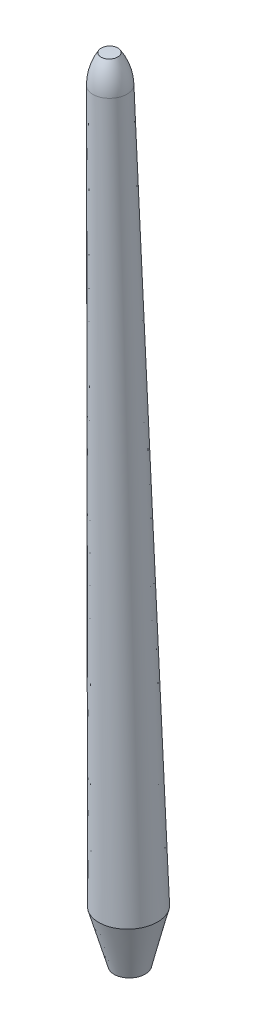
SolidWorks part; units mm, degrees
ref_plane "Alzado" through (0, 0, 0) normal (0, 0, 1) x (1, 0, 0)
ref_plane "Planta" through (0, 0, 0) normal (0, 1, 0) x (1, 0, 0)
ref_plane "Vista lateral" through (0, 0, 0) normal (1, 0, 0) x (0, 0, -1)
sketch "Croquis1" plane through (0, 0, 0) normal (0, 0, 1) x (1, 0, 0)
  line L0 (0, 0) -> (190.5, 0)
  line L1 (190.5, 0) -> (342.9736, 635)
  line L2 (0, 0) -> (-252.4067, 9652)
  line L4 (-252.4067, 9652) -> (-150.8067, 9652)
  line L5 (342.9736, 635) -> (-35.5514, 9311.6552)
  arc A1 (-35.5514, 9311.6552) -> (-150.8067, 9652) centre (-678.5233, 9283.6051) ccw
  dimension "D1" = 190.5
  dimension "D2" = 635
  dimension "D3" = 15
  dimension "D4" = 9652
  dimension "D5" = 1
revolve "Revolución2" add sketch "Croquis1" angle 360 about L2
sketch "Croquis2" plane through (0, 0, 0) normal (0, 0, 1) x (1, 0, 0)
  circle A0 centre (-252.4067, 9652) radius 3.868
  spline S0 degree 3 poles (-252.4067, 9652) (-302.7607, 9669.841) (-219.0505, 9698.0091) (-280.5989, 9758.4404) (-150.209, 9925.4508) (-331.6999, 10101.5983) (-155.4698, 10210.7517) knots 0 0 0 0 0.125238 0.194524 0.319082 1 1 1 1
